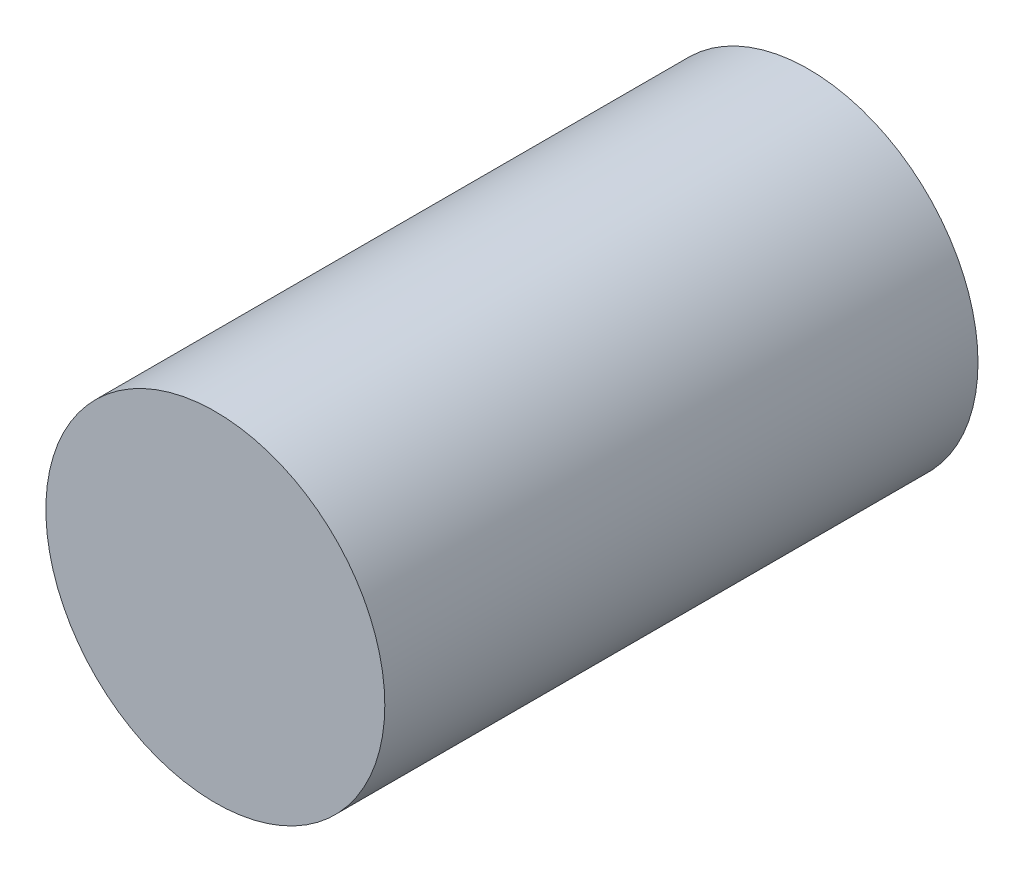
SolidWorks part; units mm, degrees
ref_plane "Front Plane" through (0, 0, 0) normal (0, 0, 1) x (1, 0, 0)
ref_plane "Top Plane" through (0, 0, 0) normal (0, 1, 0) x (1, 0, 0)
ref_plane "Right Plane" through (0, 0, 0) normal (1, 0, 0) x (0, 0, -1)
sketch "Sketch1" plane through (0, 0, 0) normal (0, 0, 1) x (1, 0, 0)
  circle A0 centre (2, 2) radius 2
  dimension "D1" = 4
extrude "Profile" add sketch "Sketch1" along normal blind 7
equation "\"Profile_Depth\"= 7mm"
equation "\"D1@Profile\" = \"Profile_Depth\""
equation "\"Profile_Sketch_1\"= 4mm"
equation "\"D1@Sketch1\" = \"Profile_Sketch_1\""
equation "\"EnvelopeWidth\"= 4mm"
equation "\"EnvelopeHeight\"= 4mm"
